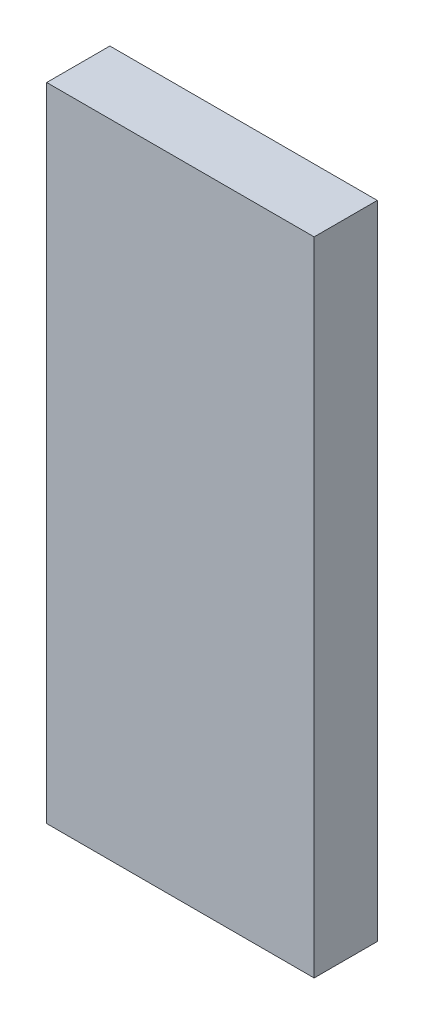
SolidWorks part; units mm, degrees
material "轻木"
ref_plane "Front" through (0, 0, 0) normal (0, 0, 1) x (1, 0, 0)
ref_plane "Top" through (0, 0, 0) normal (0, 1, 0) x (1, 0, 0)
ref_plane "Right" through (0, 0, 0) normal (1, 0, 0) x (0, 0, -1)
sketch "草图1" plane through (0, 0, 0) normal (0, 0, 1) x (1, 0, 0)
  line L1 (0, 0) -> (63.5, 0)
  line L2 (0, 0) -> (0, 152.4)
  line L3 (0, 152.4) -> (63.5, 152.4)
  line L4 (63.5, 0) -> (63.5, 152.4)
  dimension "D1" = 152.4
  dimension "D2" = 63.5
extrude "凸台-拉伸1" add sketch "草图1" along normal blind 15
